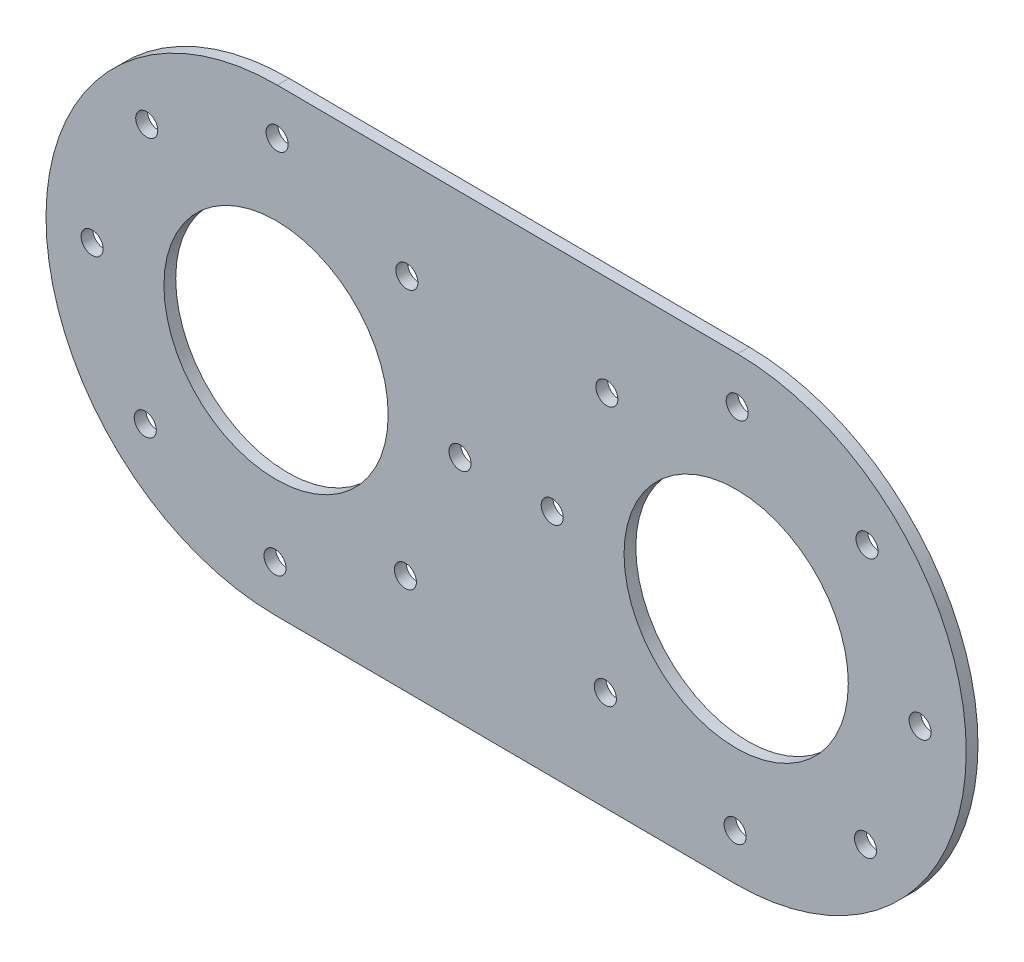
SolidWorks part; units mm, degrees
ref_plane "Front Plane" through (0, 0, 0) normal (0, 0, 1) x (1, 0, 0)
ref_plane "Top Plane" through (0, 0, 0) normal (0, 1, 0) x (1, 0, 0)
ref_plane "Right Plane" through (0, 0, 0) normal (1, 0, 0) x (0, 0, -1)
sketch "Sketch1" plane through (0, 0, 0) normal (0, 0, 1) x (1, 0, 0)
  line L0 (46.9003, -3.7607) -> (-15.6334, -3.4065)
  line L1 (0.0885, 12.1384) -> (31.3554, 11.9613)
  line L2 (-0.0885, -19.1285) -> (31.1784, -19.3056)
  circle A0 centre (31.2669, -3.6722) radius 15.6337 construction
  circle A1 centre (0, -3.4951) radius 15.6337
  circle A2 centre (0, -3.4951) radius 15.6337
  circle A3 centre (31.2669, -3.6722) radius 15.6337
  circle A6 centre (-12.5, -3.4243) radius 0.75
  circle A7 centre (-8.7888, 5.3938) radius 0.75
  circle A8 centre (0.0708, 9.0049) radius 0.75
  circle A9 centre (8.8889, 5.2937) radius 0.75
  circle A10 centre (12.5, -3.5659) radius 0.75
  circle A11 centre (8.7888, -12.384) radius 0.75
  circle A12 centre (-0.0708, -15.9951) radius 0.75
  circle A13 centre (-8.8889, -12.2838) radius 0.75
  circle A14 centre (43.7669, -3.743) radius 0.75
  circle A16 centre (40.0557, -12.5611) radius 0.75
  circle A17 centre (31.1961, -16.1722) radius 0.75
  circle A18 centre (22.378, -12.4609) radius 0.75
  circle A19 centre (18.7669, -3.6014) radius 0.75
  circle A20 centre (22.4781, 5.2167) radius 0.75
  circle A21 centre (31.3377, 8.8278) radius 0.75
  circle A22 centre (40.1558, 5.1166) radius 0.75
  circle A23 centre (0, -3.4951) radius 7.62
  circle A24 centre (31.2669, -3.6722) radius 7.62
  point P7 (31.2669, -3.6722)
  point P8 (0, -3.4951)
  point P28 (0, -3.4951)
  point P46 (31.2669, -3.6722)
  dimension "D2" = 12.5
  dimension "D4" = 12.5
  dimension "D5" = 1.5
  dimension "D6" = 1.5
  dimension "D8" = 15.24
  dimension "D9" = 15.24
  dimension "D1" = 0
  dimension "D3" = 8
  dimension "D7" = 8
extrude "Boss-Extrude1" add sketch "Sketch1" along normal blind 0.8 contours A19 L0 A3 A14 A18 A17 A16 | A19 L0 A14 A3 A22 A21 A20 | A10 L0 A2 A6 A9 A8 A7 | A10 L0 A6 A2 A13 A12 A11 | A3 L1 A2 | A3 A2 L2
